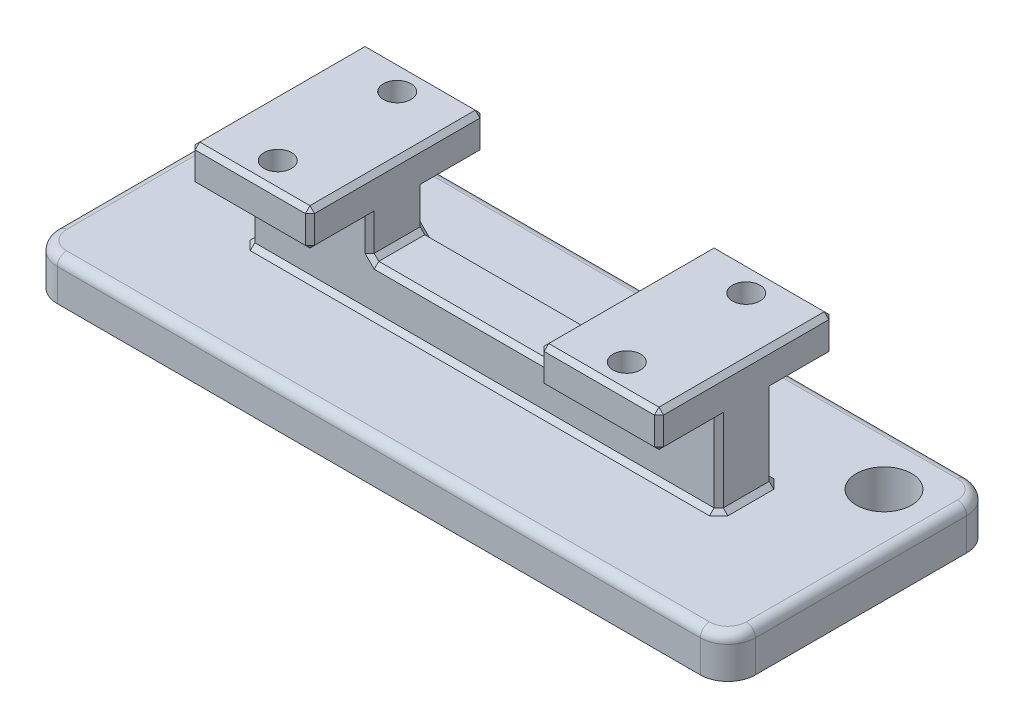
SolidWorks part; units mm, degrees
material "AISI 1020"
ref_plane "Front Plane" through (0, 0, 0) normal (0, 0, 1) x (1, 0, 0)
ref_plane "Top Plane" through (0, 0, 0) normal (0, 1, 0) x (1, 0, 0)
ref_plane "Right Plane" through (0, 0, 0) normal (1, 0, 0) x (0, 0, -1)
sketch "Sketch1" plane through (0, 0, 0) normal (0, 1, 0) x (1, 0, 0)
  line L1 (-35, -14.5) -> (35, -14.5)
  line L2 (-38, -11.5) -> (-38, 11.5)
  line L3 (-35, 14.5) -> (35, 14.5)
  line L4 (38, -11.5) -> (38, 11.5)
  line L5 (-38, -14.5) -> (38, 14.5) construction
  line L6 (-38, 14.5) -> (38, -14.5) construction
  circle A0 centre (-32, 8.5) radius 3
  circle A1 centre (32, 8.5) radius 3
  arc A4 (-35, -14.5) -> (-38, -11.5) centre (-35, -11.5) cw
  arc A5 (35, -14.5) -> (38, -11.5) centre (35, -11.5) ccw
  arc A6 (35, 14.5) -> (38, 11.5) centre (35, 11.5) cw
  arc A7 (-38, 11.5) -> (-35, 14.5) centre (-35, 11.5) cw
  point P0 (0, 0)
  dimension "D1" = 3
  dimension "D2" = 6
  dimension "D3" = 6
  dimension "D4" = 6
  dimension "D5" = 6
  dimension "D6" = 14.5
  dimension "D7" = 64
extrude "Boss-Extrude1" add sketch "Sketch1" along normal blind 4.5
sketch "Sketch2" plane through (0, 0, 0) normal (1, 0, 0) x (0, 0, -1)
  line L0 (-3, 4.5) -> (-3, 13.5)
  line L1 (-11.5, 4.5) -> (11.5, 4.5) construction
  line L2 (-3, 13.5) -> (-9.5, 13.5)
  line L3 (-9.5, 13.5) -> (-9.5, 17.5)
  line L4 (-9.5, 17.5) -> (9.5, 17.5)
  line L5 (9.5, 17.5) -> (9.5, 13.5)
  line L6 (9.5, 13.5) -> (3, 13.5)
  line L7 (3, 13.5) -> (3, 4.5)
  line L8 (3, 4.5) -> (-3, 4.5)
  line L9 (-11.5, 0) -> (11.5, 0) construction
  line L10 (-14.5, 4.5) -> (-14.5, 0) construction
  point P14 (0, 4.5)
  dimension "D1" = 17.5
  dimension "D2" = 9
  dimension "D3" = 6.5
  dimension "D4" = 11.5
extrude "Boss-Extrude2" add sketch "Sketch2" along normal offset from surface 12.5 and the other way offset from surface (25.5 mm away) 12.5 up to face at (38, 2.25, 0) other way up to face at (-38, 2.25, 0)
sketch "Sketch3" plane through (0, 0, 0) normal (0, 0, 1) x (1, 0, 0)
  line L0 (25.5, 17.5) -> (-25.5, 17.5) construction
  line L1 (-12.5, 25.5) -> (12.5, 25.5)
  line L2 (-12.5, 25.5) -> (-12.5, 9.5)
  line L3 (-12.5, 9.5) -> (12.5, 9.5)
  line L4 (12.5, 25.5) -> (12.5, 9.5)
  line L5 (-12.5, 25.5) -> (12.5, 9.5) construction
  line L6 (-12.5, 9.5) -> (12.5, 25.5) construction
  point P0 (0, 17.5)
  dimension "D1" = 25
  dimension "D2" = 8
extrude "Cut-Extrude1" cut sketch "Sketch3" against normal up to vertex (9.5 mm away) and the other way up to vertex (9.5 mm away)
sketch "Sketch4" plane through (0, 17.5, 0) normal (0, 1, 0) x (1, 0, 0)
  line L1 (-38, 11.5) -> (-38, -11.5) construction
  line L2 (38, -11.5) -> (38, 11.5) construction
  circle A0 centre (-19, 6.5) radius 1.5
  circle A1 centre (-19, -6.5) radius 1.5
  circle A2 centre (19, -6.5) radius 1.5
  circle A3 centre (19, 6.5) radius 1.5
  dimension "D1" = 3
  dimension "D2" = 19
  dimension "D3" = 19
  dimension "D4" = 6.5
  dimension "D5" = 6.5
extrude "Cut-Extrude2" cut sketch "Sketch4" against normal up to next
fillet "Fillet1" radius 1 8 edges at (-37.1213, 4.5, 13.6213) (-38, 4.5, 0) (-37.1213, 4.5, -13.6213) (0, 4.5, -14.5) (37.1213, 4.5, -13.6213) (38, 4.5, 0) (37.1213, 4.5, 13.6213) (0, 4.5, 14.5)
chamfer "Chamfer1" distance 0.5 angle 45 44 edges at (19, 17.5, -9.5) (19, 13.5, -9.5) (19, 13.5, 9.5) (25.5, 4.5, 0) (25.5, 9, 3) (25.5, 13.5, 6.25) (25.5, 15.5, 9.5) (25.5, 9, -3) (25.5, 13.5, -6.25) (25.5, 15.5, -9.5) (25.5, 17.5, 0) (19, 17.5, 9.5) (12.5, 11.5, 3) (12.5, 9.5, 0) (12.5, 11.5, -3) (12.5, 13.5, -6.25) (12.5, 15.5, -9.5) (12.5, 17.5, 0) (12.5, 15.5, 9.5) (12.5, 13.5, 6.25) (0, 9.5, 3) (0, 9.5, -3) (0, 4.5, -3) (0, 4.5, 3) (-19, 13.5, -9.5) (-19, 17.5, -9.5) (-19, 17.5, 9.5) (-12.5, 11.5, 3) (-12.5, 13.5, 6.25) (-12.5, 9.5, 0) (-12.5, 11.5, -3) (-12.5, 13.5, -6.25) (-12.5, 15.5, -9.5) (-12.5, 17.5, 0) (-12.5, 15.5, 9.5) (-19, 13.5, 9.5) (-25.5, 9, -3) (-25.5, 13.5, -6.25) (-25.5, 15.5, -9.5) (-25.5, 17.5, 0) (-25.5, 15.5, 9.5) (-25.5, 13.5, 6.25) (-25.5, 9, 3) (-25.5, 4.5, 0)
